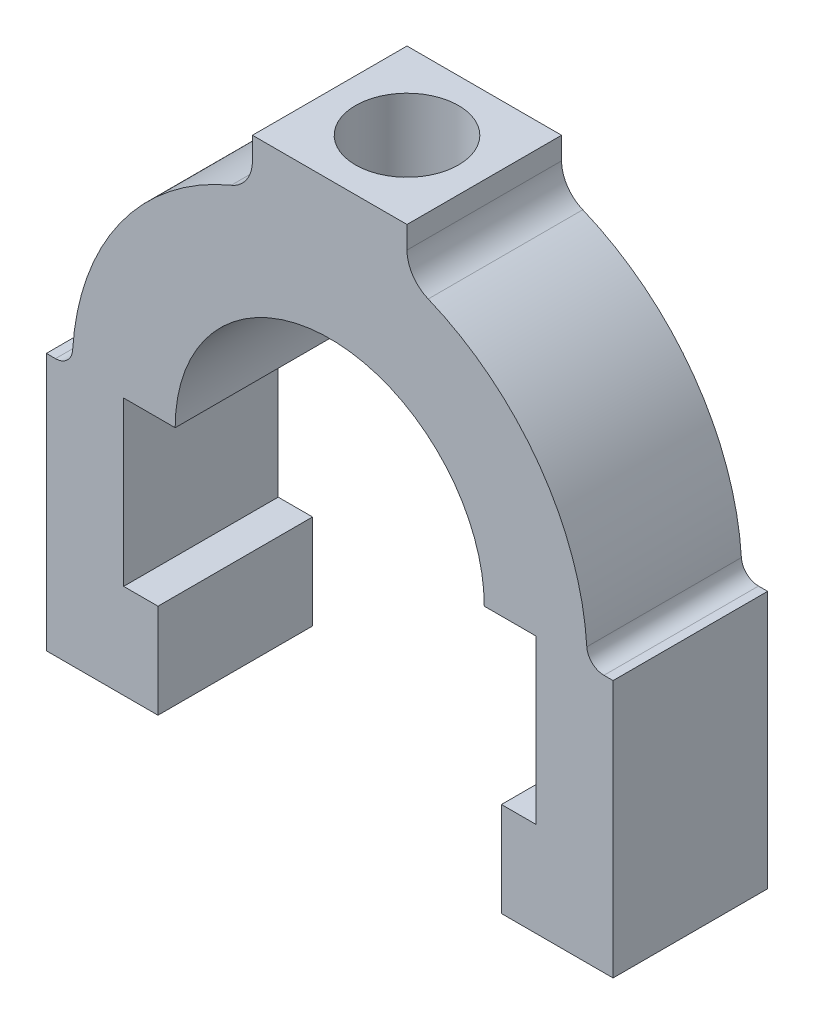
SolidWorks part; units mm, degrees
ref_plane "Front Plane" through (0, 0, 0) normal (0, 0, 1) x (1, 0, 0)
ref_plane "Top Plane" through (0, 0, 0) normal (0, 1, 0) x (1, 0, 0)
ref_plane "Right Plane" through (0, 0, 0) normal (1, 0, 0) x (0, 0, -1)
sketch "Sketch1" plane through (0, 0, 0) normal (0, 0, 1) x (1, 0, 0)
  line L0 (-18, 0) -> (-24, 0)
  line L1 (-24, 0) -> (-24, -19)
  line L2 (-24, -19) -> (-20, -19)
  line L3 (-20, -19) -> (-20, -30)
  line L4 (-20, -30) -> (-33, -30)
  line L5 (-33, -30) -> (-33, 0)
  line L6 (-33, 0) -> (-30, 0)
  line L7 (0, -55) -> (0, 55) construction
  line L8 (20, -30) -> (33, -30)
  line L9 (20, -19) -> (20, -30)
  line L10 (24, -19) -> (20, -19)
  line L11 (24, 0) -> (24, -19)
  line L12 (18, 0) -> (24, 0)
  line L13 (33, 0) -> (30, 0)
  line L14 (33, -30) -> (33, 0)
  line L15 (0, 0) -> (0, -29.1439) construction
  line L16 (-9, 28.6182) -> (-9, 34)
  line L17 (-9, 34) -> (9, 34)
  line L18 (9, 34) -> (9, 28.6182)
  arc A0 (30, 0) -> (9, 28.6182) centre (0, 0) ccw
  arc A1 (18, 0) -> (-18, 0) centre (0, 0) ccw
  arc A2 (-9, 28.6182) -> (-30, 0) centre (0, 0) ccw
  arc A3 (30, 0) -> (-30, 0) centre (0, 0) ccw construction
  dimension "D1" = 30
  dimension "D3" = 9
  dimension "D4" = 13
  dimension "D5" = 33
  dimension "D6" = 11
  dimension "D7" = 30
  dimension "D8" = 64
  dimension "D9" = 18
  dimension "D2" = 12
extrude "Boss-Extrude1" add sketch "Sketch1" along normal mid plane 18
fillet "Fillet1" radius 4 2 edges at (-9, 28.6182, 0) (9, 28.6182, 0)
fillet "Fillet2" radius 2 2 edges at (30, 0, 0) (-30, 0, 0)
hole_wizard "Hole1" positions "Sketch2" profile "Sketch3" legacy end condition up to next
sketch "Sketch2" plane through (0, 34, 0) normal (0, 1, 0) x (1, 0, 0)
  point P0 (0, 0)
sketch "Sketch3" plane through (0, 34, 0) normal (1, 0, 0) x (0, 0, 1)
  line L0 (0, 0) -> (0, 16)
  line L1 (0, 16) -> (6, 16)
  line L2 (6, 16) -> (6, 0)
  line L3 (6, 0) -> (0, 0)
  line L4 (0, 110) -> (0, -10) construction
  dimension "Diameter" = 12
  dimension "Depth" = 16
